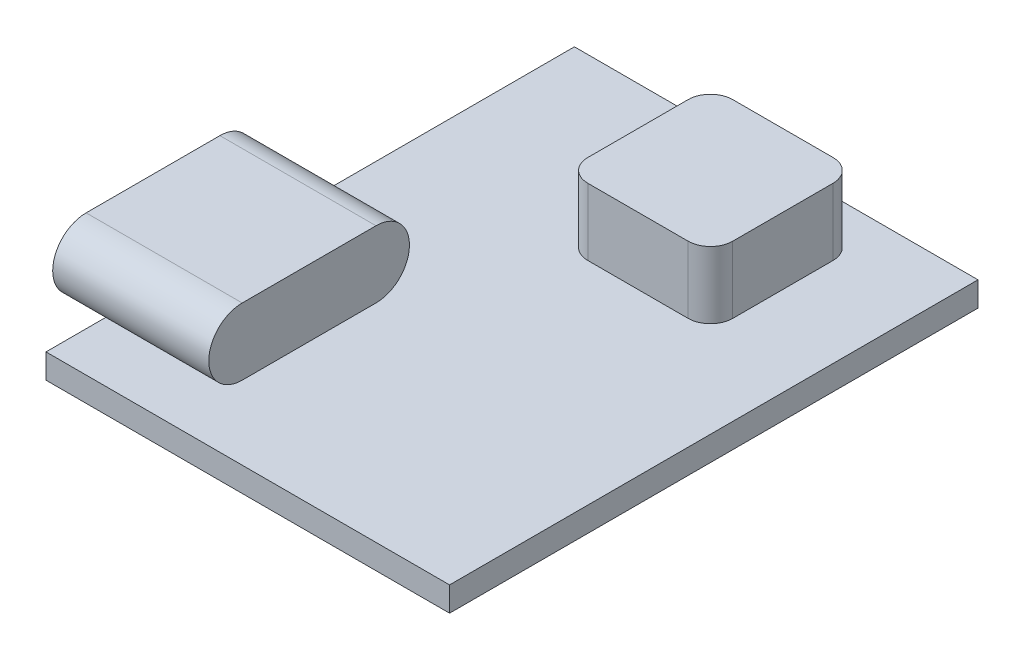
SolidWorks part; units mm, degrees
material "ABS"
ref_plane "Front Plane" through (0, 0, 0) normal (0, 0, 1) x (1, 0, 0)
ref_plane "Top Plane" through (0, 0, 0) normal (0, 1, 0) x (1, 0, 0)
ref_plane "Right Plane" through (0, 0, 0) normal (1, 0, 0) x (0, 0, -1)
sketch "Sketch1" plane through (0, 0, 0) normal (0, 1, 0) x (1, 0, 0)
  line L1 (-9.05, 11.85) -> (9.05, 11.85)
  line L2 (-9.05, 11.85) -> (-9.05, -11.85)
  line L3 (-9.05, -11.85) -> (9.05, -11.85)
  line L4 (9.05, 11.85) -> (9.05, -11.85)
  line L5 (0, -11.85) -> (0, 11.85) construction
  line L6 (-9.05, 0) -> (9.05, 0) construction
  point P0 (0, 0)
  dimension "D1" = 18.1
  dimension "D2" = 23.7
extrude "Boss-Extrude1" add sketch "Sketch1" along normal blind 1.1
sketch "Sketch3" plane through (-9.05, 0, 0) normal (-1, 0, 0) x (0, 0, 1)
  line L0 (2.55, 2.6) -> (8.55, 2.6) construction
  line L1 (2.55, 4.1) -> (8.55, 4.1)
  line L2 (2.55, 1.1) -> (8.55, 1.1)
  line L3 (-11.85, 1.1) -> (11.85, 1.1) construction
  line L4 (11.85, 1.1) -> (11.85, 0) construction
  arc A0 (2.55, 4.1) -> (2.55, 1.1) centre (2.55, 2.6) ccw
  arc A1 (8.55, 1.1) -> (8.55, 4.1) centre (8.55, 2.6) ccw
  point P2 (5.55, 2.6)
  point P7 (1.05, 2.6)
  point P8 (10.05, 2.6)
  dimension "D1" = 9
  dimension "D2" = 3
  dimension "D3" = 6.3
extrude "Boss-Extrude2" add sketch "Sketch3" along normal blind 1.5 and the other way blind 5.5 separate body
shell "Shell1" thickness 0.3
sketch "Sketch4" plane through (0, 1.1, 0) normal (0, 1, 0) x (1, 0, 0)
  line L0 (9.05, 11.85) -> (-9.05, 11.85) construction
  line L1 (-1.45, 10.35) -> (5.05, 10.35)
  line L2 (-1.45, 10.35) -> (-1.45, 3.85)
  line L3 (-1.45, 3.85) -> (5.05, 3.85)
  line L4 (5.05, 10.35) -> (5.05, 3.85)
  line L5 (9.05, -11.85) -> (9.05, 11.85) construction
  dimension "D1" = 6.5
  dimension "D2" = 1.5
  dimension "D3" = 4
extrude "Boss-Extrude3" add sketch "Sketch4" along normal blind 3 separate body
fillet "Fillet1" radius 1 4 edges at (5.05, 2.6, -10.35) (-1.45, 2.6, -10.35) (-1.45, 2.6, -3.85) (5.05, 2.6, -3.85)
